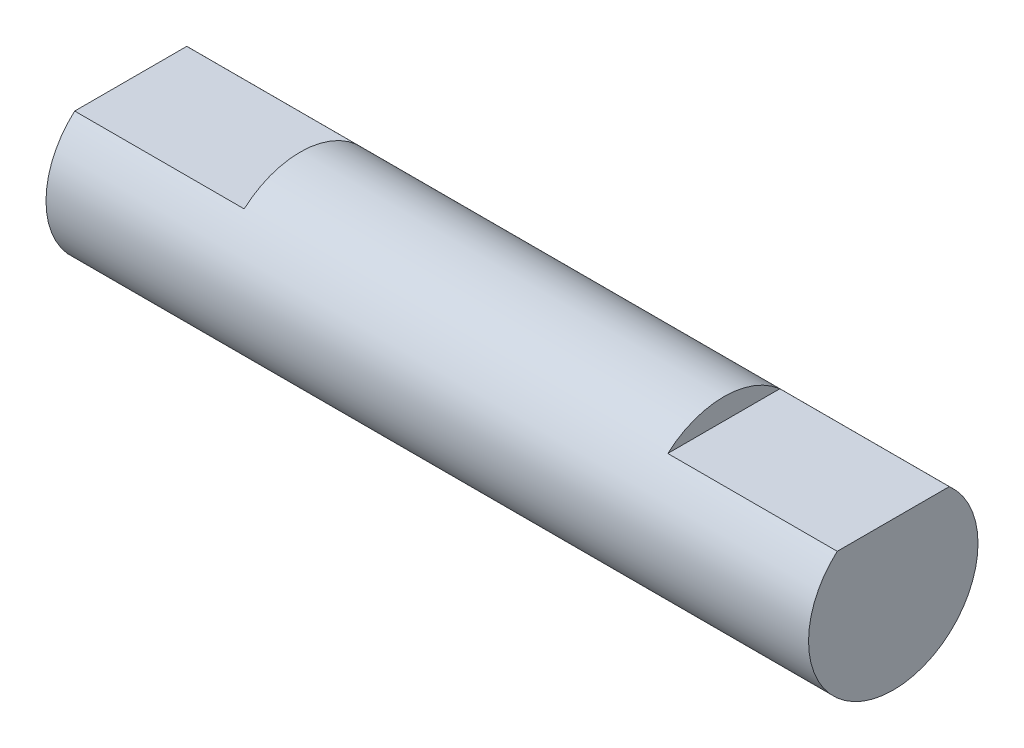
SolidWorks part; units mm, degrees
ref_plane "Front Plane" through (0, 0, 0) normal (0, 0, 1) x (1, 0, 0)
ref_plane "Top Plane" through (0, 0, 0) normal (0, 1, 0) x (1, 0, 0)
ref_plane "Right Plane" through (0, 0, 0) normal (1, 0, 0) x (0, 0, -1)
sketch "Sketch1" plane through (0, 0, 0) normal (1, 0, 0) x (0, 0, -1)
  circle A0 centre (0, 0) radius 3.175
  dimension "D1" = 6.35
extrude "Boss-Extrude1" add sketch "Sketch1" along normal blind 28.575
sketch "Sketch2" plane through (28.575, 0, 0) normal (1, 0, 0) x (0, 0, -1)
  line L0 (0, 0) -> (0, 2.3813) construction
  line L1 (-4.7625, 2.3813) -> (4.7625, 2.3813)
  line L2 (-4.7625, 2.3813) -> (-4.7625, 3.9688)
  line L3 (-4.7625, 3.9688) -> (4.7625, 3.9688)
  line L4 (4.7625, 2.3813) -> (4.7625, 3.9688)
  dimension "D1" = 2.3813
  dimension "D2" = 1.5875
  dimension "D3" = 9.525
extrude "Cut-Extrude1" cut sketch "Sketch2" against normal blind 6.35
ref_plane "Plane1" through (14.2875, 0, 0) normal (1, 0, 0) x (0, 0, -1)
mirror "Mirror1" about plane through (14.2875, 0, 0) normal (1, 0, 0) of "Cut-Extrude1"
